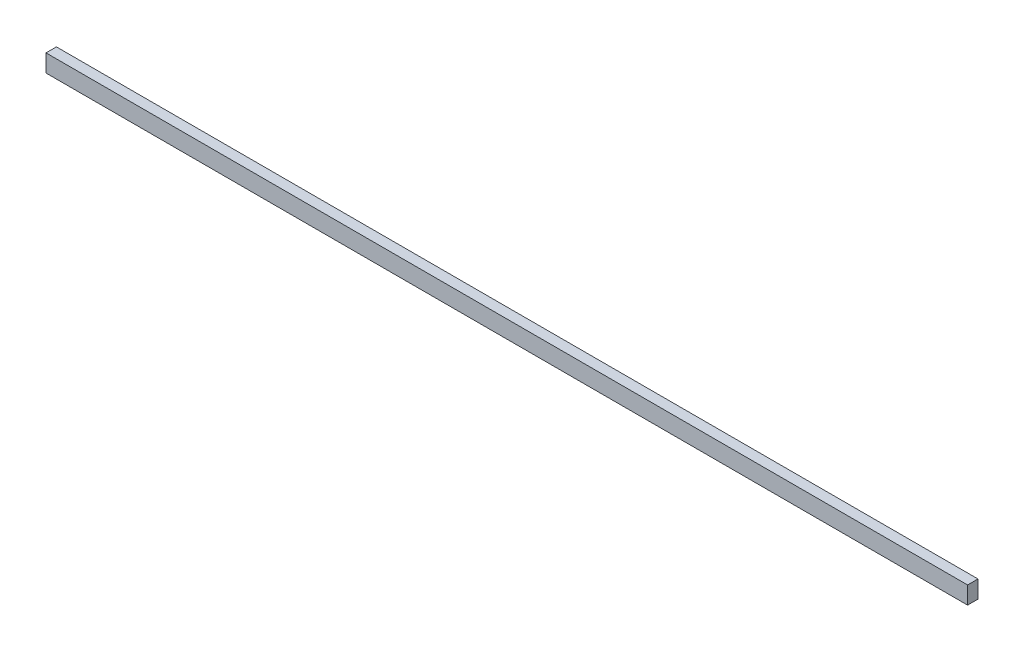
SolidWorks part; units mm, degrees
ref_plane "Plan de face" through (0, 0, 0) normal (0, 0, 1) x (1, 0, 0)
ref_plane "Plan de dessus" through (0, 0, 0) normal (0, 1, 0) x (1, 0, 0)
ref_plane "Plan de droite" through (0, 0, 0) normal (1, 0, 0) x (0, 0, -1)
sketch "Esquisse1" plane through (0, 0, 0) normal (0, 0, 1) x (1, 0, 0)
  line L1 (0, 0) -> (1950, 0)
  line L2 (0, 0) -> (0, 37)
  line L3 (0, 37) -> (1950, 37)
  line L4 (1950, 0) -> (1950, 37)
  dimension "D1" = 37
  dimension "D2" = 1950
extrude "Boss.-Extru.1" add sketch "Esquisse1" along normal blind 22
